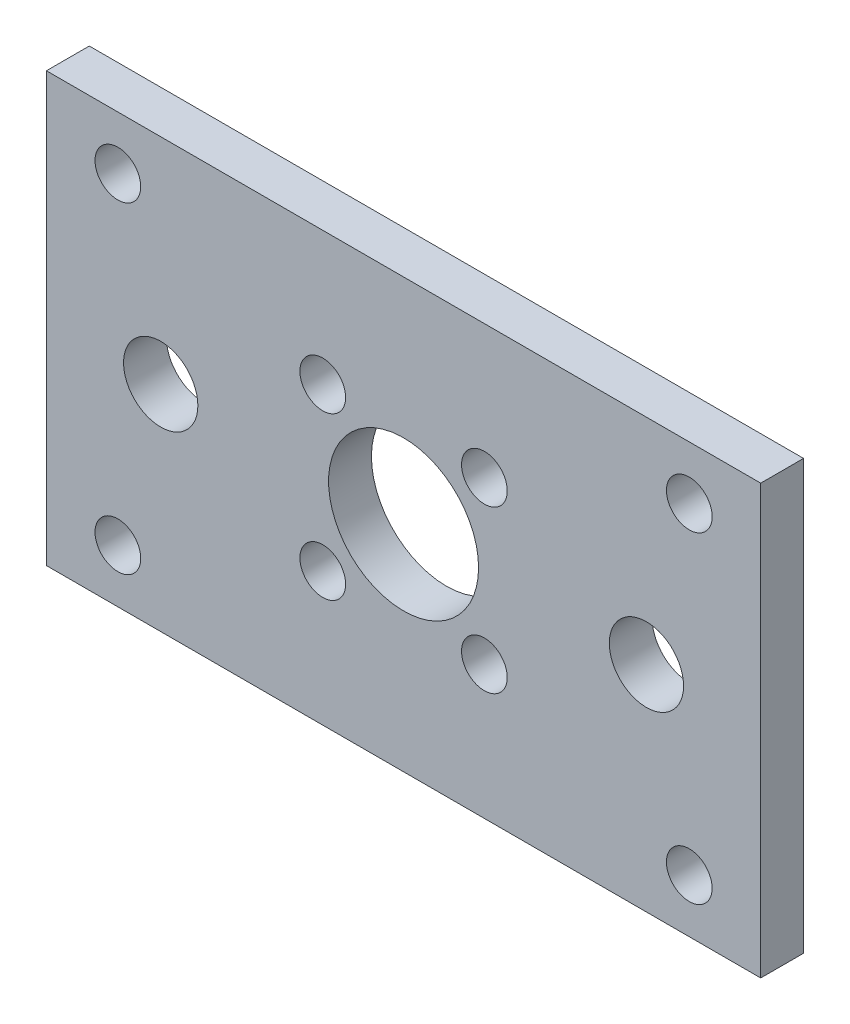
SolidWorks part; units mm, degrees
material "Thornel Mat VMA"
ref_plane "前视基准面" through (0, 0, 0) normal (0, 0, 1) x (1, 0, 0)
ref_plane "上视基准面" through (0, 0, 0) normal (0, 1, 0) x (1, 0, 0)
ref_plane "右视基准面" through (0, 0, 0) normal (1, 0, 0) x (0, 0, -1)
sketch "草图1" plane through (0, 0, 0) normal (0, 0, 1) x (1, 0, 0)
  line L0 (0, 15) -> (50, 15) construction
  line L2 (0, 0) -> (0, 30)
  line L4 (50, 0) -> (50, 30)
  line L9 (25, 30) -> (25, -1.3654) construction
  line L19 (0, 30) -> (50, 30)
  line L20 (50, 0) -> (0, 0)
  dimension "D1" = 50
  dimension "D2" = 30
extrude "凸台-拉伸1" add sketch "草图1" along normal blind 3
sketch "草图2" plane through (0, 0, 3) normal (0, 0, 1) x (1, 0, 0)
  line L0 (0, 15) -> (50, 15) construction
  line L1 (0, 30) -> (0, 0) construction
  line L2 (50, 0) -> (50, 30) construction
  line L3 (25, 15) -> (25, 32.3044) construction
  line L4 (30.6569, 20.6569) -> (25, 15) construction
  line L5 (45, 33.6346) -> (45, -4.3654) construction
  circle A0 centre (8, 15) radius 2.6
  circle A1 centre (42, 15) radius 2.6
  circle A2 centre (25, 15) radius 8 construction
  circle A3 centre (30.6569, 20.6569) radius 1.6
  circle A4 centre (30.6569, 9.3431) radius 1.6
  circle A5 centre (19.3431, 9.3431) radius 1.6
  circle A6 centre (19.3431, 20.6569) radius 1.6
  circle A7 centre (25, 15) radius 5.25
  circle A8 centre (45, 3.7346) radius 1.6
  circle A9 centre (45, 26.2654) radius 1.6
  circle A10 centre (5, 26.2654) radius 1.6
  circle A11 centre (5, 3.7346) radius 1.6
  point P25 (25, 15)
  dimension "D1" = 34
  dimension "D3" = 5.2
  dimension "D4" = 5.2
  dimension "D5" = 16
  dimension "D6" = 3.2
  dimension "D9" = 10.5
  dimension "D10" = 3.2
  dimension "D2" = 8
  dimension "D7" = 45
  dimension "D8" = 4
extrude "切除-拉伸1" cut sketch "草图2" against normal blind 5
